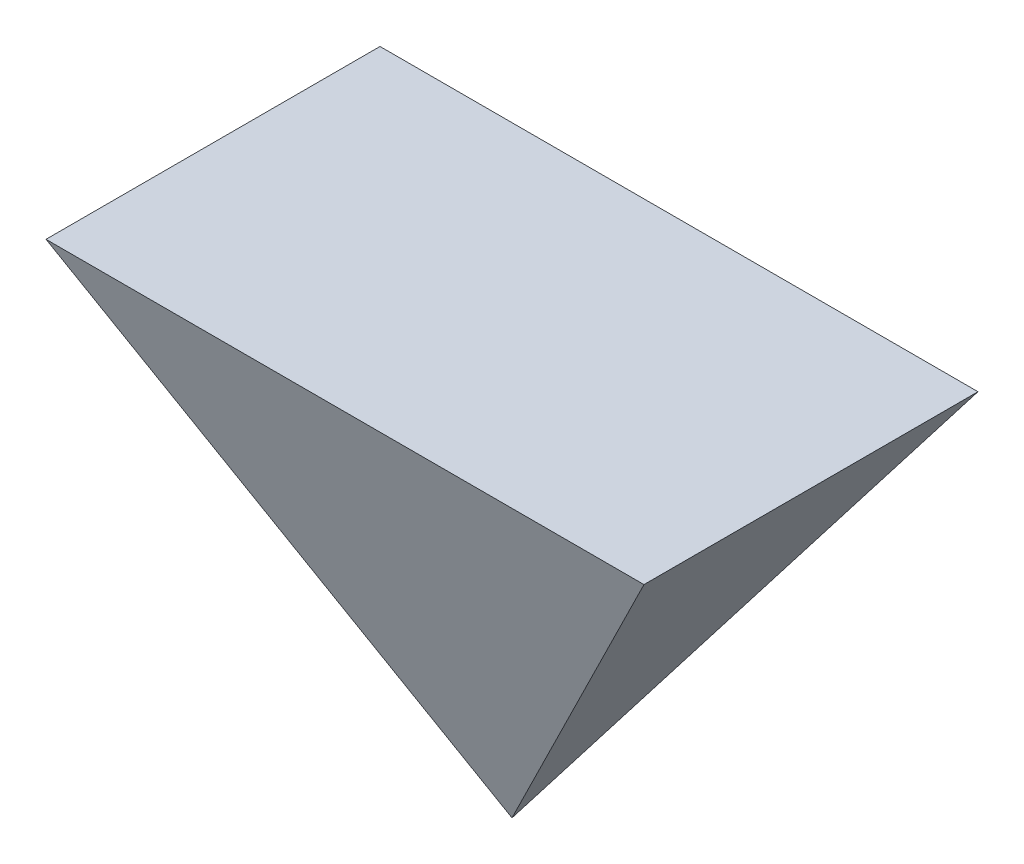
SolidWorks part; units mm, degrees
ref_plane "Front Plane" through (0, 0, 0) normal (0, 0, 1) x (1, 0, 0)
ref_plane "Top Plane" through (0, 0, 0) normal (0, 1, 0) x (1, 0, 0)
ref_plane "Right Plane" through (0, 0, 0) normal (1, 0, 0) x (0, 0, -1)
sketch "StartSquare" plane through (0, 0, 0) normal (0, 1, 0) x (1, 0, 0)
  line L5 (-1.3644, 0.7749) -> (1.3644, 0.7749)
  line L6 (-1.3644, 0.7749) -> (-1.3644, -0.7749)
  line L7 (-1.3644, -0.7749) -> (1.3644, -0.7749)
  line L8 (1.3644, 0.7749) -> (1.3644, -0.7749)
  line L9 (-1.3644, 0.7749) -> (1.3644, -0.7749) construction
  line L10 (-1.3644, -0.7749) -> (1.3644, 0.7749) construction
  point P0 (0, 0)
  dimension "D1" = 2.7288
  dimension "D2" = 1.5498
ref_plane "End" through (0, 1500, 0) normal (0, 1, 0) x (1, 0, 0)
sketch "EndSquare" plane through (0, 1500, 0) normal (0, 1, 0) x (1, 0, 0)
  line L1 (-1032.2858, 576.571) -> (1032.2858, 576.571)
  line L2 (-1032.2858, 576.571) -> (-1032.2858, -576.571)
  line L3 (-1032.2858, -576.571) -> (1032.2858, -576.571)
  line L4 (1032.2858, 576.571) -> (1032.2858, -576.571)
  line L5 (-1032.2858, 576.571) -> (1032.2858, -576.571) construction
  line L6 (-1032.2858, -576.571) -> (1032.2858, 576.571) construction
  point P0 (0, 0)
  dimension "D1" = 2064.5717
  dimension "D2" = 1153.1419
loft "Frustum" add profiles "StartSquare", "EndSquare"
